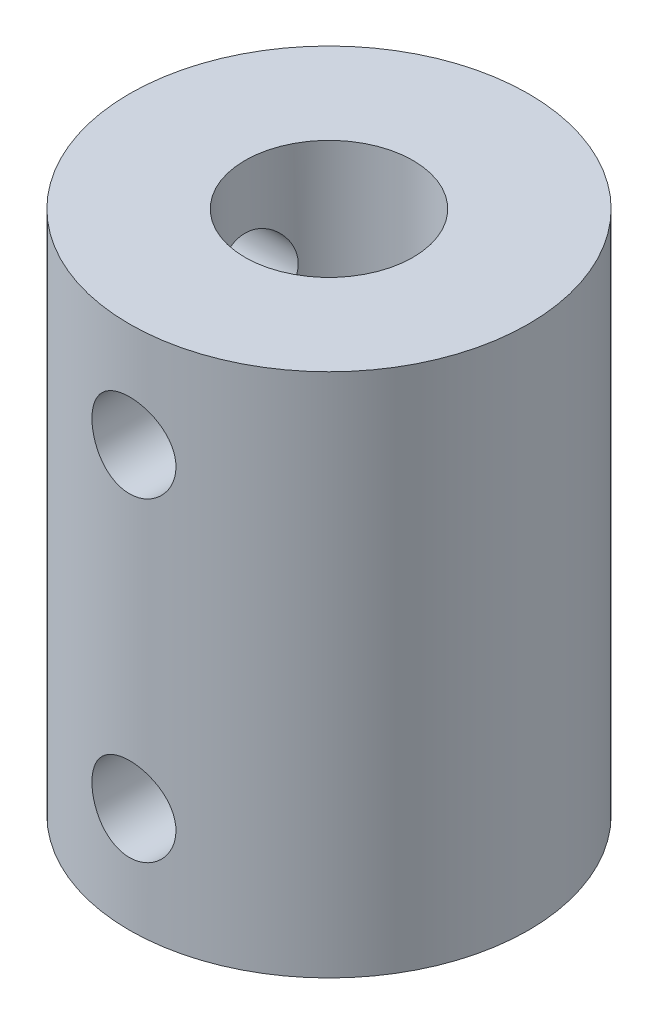
SolidWorks part; units mm, degrees
ref_plane "Front Plane" through (0, 0, 0) normal (0, 0, 1) x (1, 0, 0)
ref_plane "Top Plane" through (0, 0, 0) normal (0, 1, 0) x (1, 0, 0)
ref_plane "Right Plane" through (0, 0, 0) normal (1, 0, 0) x (0, 0, -1)
sketch "Sketch1" plane through (0, 0, 0) normal (0, 1, 0) x (1, 0, 0)
  circle A0 centre (0, 0) radius 9.5
extrude "Boss-Extrude1" add sketch "Sketch1" along normal blind 25
sketch "Sketch2" plane through (0, 25, 0) normal (0, 1, 0) x (1, 0, 0)
  circle A0 centre (0, 0) radius 4
extrude "Cut-Extrude1" cut sketch "Sketch2" against normal blind 25
sketch "Sketch3" plane through (0, 0, 0) normal (0, 0, 1) x (1, 0, 0)
  circle A0 centre (0, 20) radius 2
  circle A1 centre (0, 5) radius 2
extrude "Cut-Extrude2" cut sketch "Sketch3" along normal blind 10
sketch "Sketch4" plane through (0, 0, 0) normal (1, 0, 0) x (0, 0, -1)
  circle A0 centre (0, 20) radius 2
  circle A1 centre (0, 5) radius 2
extrude "Cut-Extrude3" cut sketch "Sketch4" against normal blind 10
